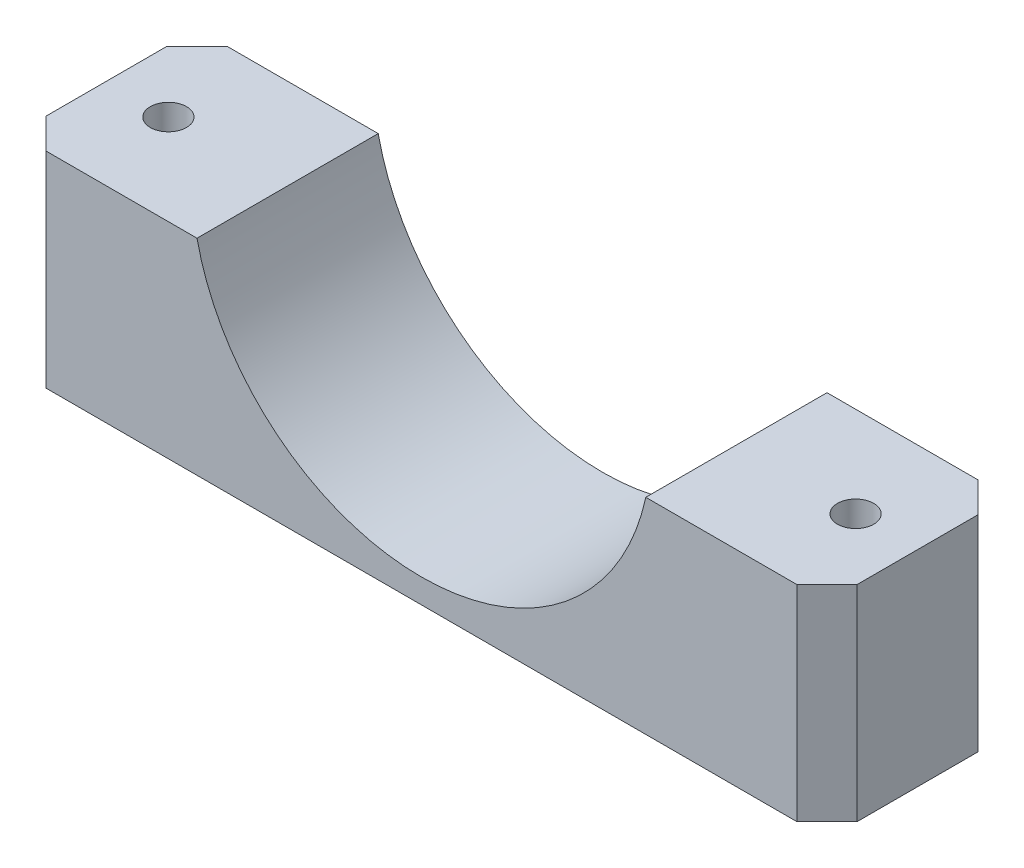
SolidWorks part; units mm, degrees
ref_plane "Front Plane" through (0, 0, 0) normal (0, 0, 1) x (1, 0, 0)
ref_plane "Top Plane" through (0, 0, 0) normal (0, 1, 0) x (1, 0, 0)
ref_plane "Right Plane" through (0, 0, 0) normal (1, 0, 0) x (0, 0, -1)
sketch "Sketch1" plane through (0, 0, 0) normal (0, 0, 1) x (1, 0, 0)
  line L0 (-18.5742, -4) -> (-33.5742, -4)
  line L1 (-33.5742, -4) -> (-33.5742, -21)
  line L2 (-33.5742, -21) -> (33.5742, -21)
  line L3 (33.5742, -21) -> (33.5742, -4)
  line L4 (33.5742, -4) -> (18.5742, -4)
  arc A0 (-18.5742, -4) -> (18.5742, -4) centre (0, 0) ccw
  dimension "D1" = 19
  dimension "D2" = 15
  dimension "D3" = 15
  dimension "D4" = 21
  dimension "D5" = 4
extrude "Boss-Extrude1" add sketch "Sketch1" along normal blind 15 contours L4 A0 L0 L1 L2 L3
chamfer "Chamfer1" distance 2.5 4 edges at (33.5742, -12.5, 0) (33.5742, -12.5, 15) (-33.5742, -12.5, 0) (-33.5742, -12.5, 15)
sketch "Sketch2" plane through (0, -4, 0) normal (0, 1, 0) x (1, 0, 0)
  line L0 (0, -8.25) -> (0, 8.25) construction
  circle A0 centre (28.4416, -7.5) radius 1.4
  circle A1 centre (-28.4416, -7.5) radius 1.4
  dimension "D1" = 2.8
extrude "Cut-Extrude1" cut sketch "Sketch2" against normal through all
hole_wizard "Ø3.0mm Dowel Hole1" positions "Sketch3" profile "Sketch4" hole size "Ø3.0" standard "ANSI Metric"
sketch "Sketch3" plane through (0, -4, 0) normal (0, 1, 0) x (1, 0, 0)
  point P0 (-28.4416, -7.5)
  point P3 (28.4416, -7.5)
sketch "Sketch4" plane through (-28.4416, -4, 7.5) normal (1, 0, 0) x (0, 0, 1)
  line L0 (0, 0) -> (0, 32)
  line L1 (0, 32) -> (1.5, 31.0987)
  line L2 (1.5, 31.0987) -> (1.5, 0)
  line L5 (1.5, 0) -> (0, 0)
  line L10 (0, 32) -> (-1.5, 31.0987) construction
  line L11 (0, -6.35) -> (0, 107.95) construction
  dimension "Hole Dia." = 3
  dimension "Hole Depth" = 32
  dimension "Drill Angle" = 118
